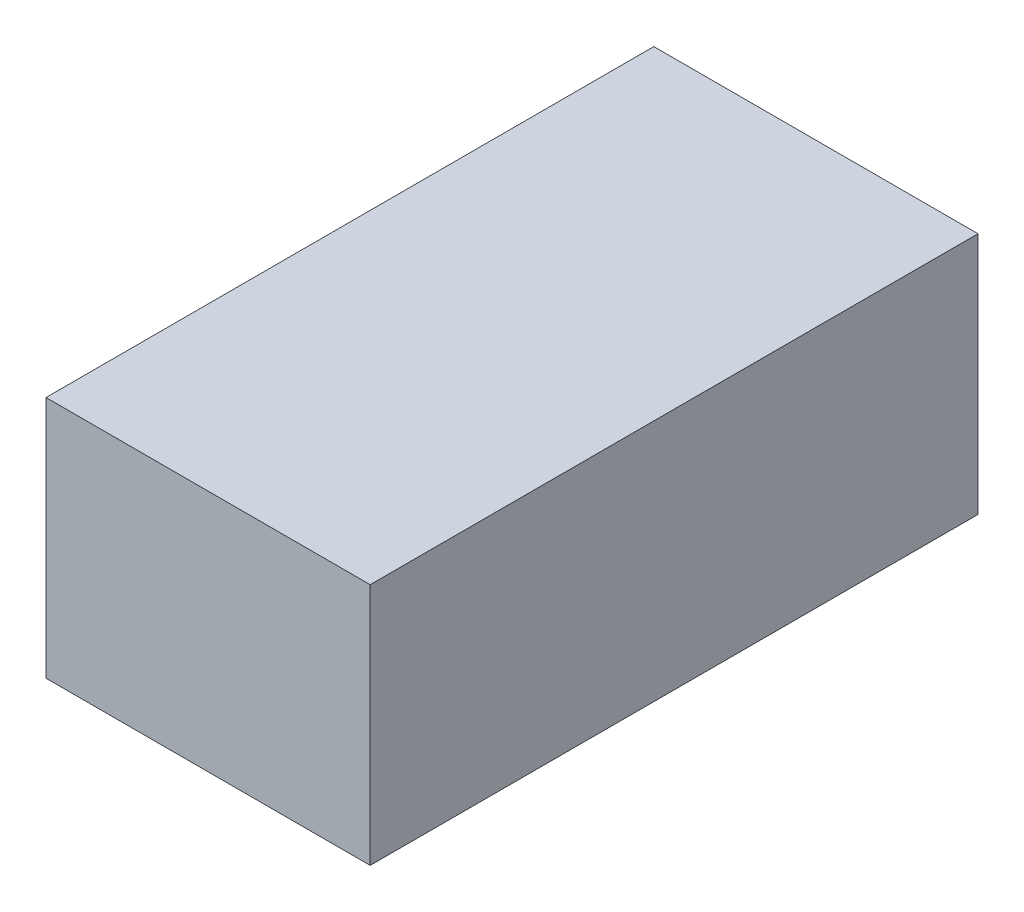
SolidWorks part; units mm, degrees
ref_plane "Front Plane" through (0, 0, 0) normal (0, 0, 1) x (1, 0, 0)
ref_plane "Top Plane" through (0, 0, 0) normal (0, 1, 0) x (1, 0, 0)
ref_plane "Right Plane" through (0, 0, 0) normal (1, 0, 0) x (0, 0, -1)
sketch "Sketch1" plane through (0, 0, 0) normal (1, 0, 0) x (0, 0, -1)
  line L1 (-7.5, 3) -> (7.5, 3)
  line L2 (-7.5, 3) -> (-7.5, -3)
  line L3 (-7.5, -3) -> (7.5, -3)
  line L4 (7.5, 3) -> (7.5, -3)
  line L5 (-7.5, 3) -> (7.5, -3) construction
  line L6 (-7.5, -3) -> (7.5, 3) construction
  point P0 (0, 0)
  dimension "D1" = 15
  dimension "D2" = 6
extrude "Boss-Extrude1" add sketch "Sketch1" along normal mid plane 8
